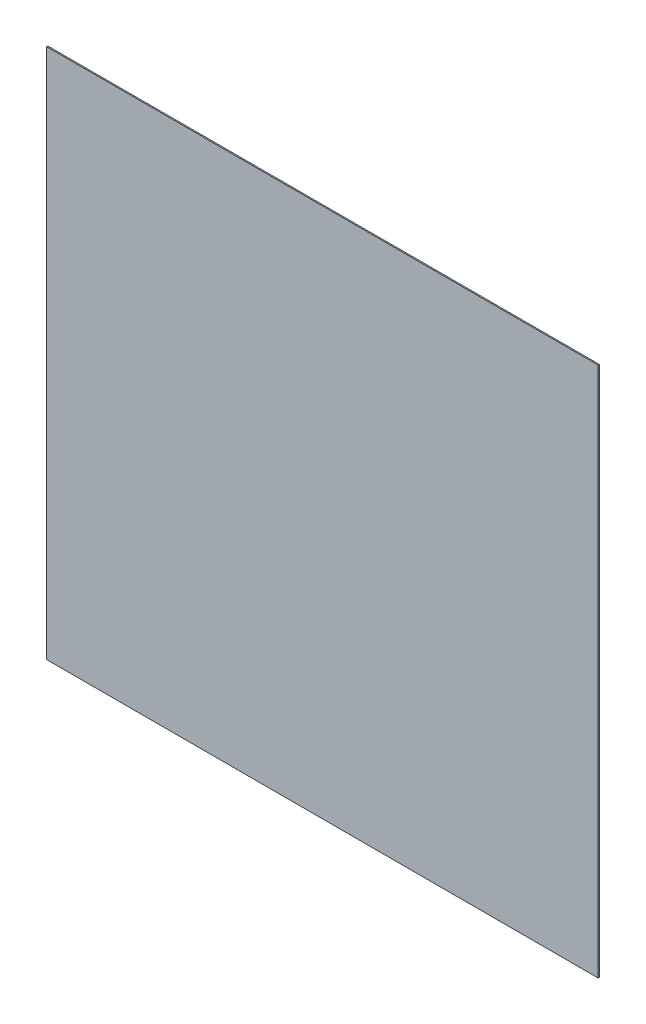
SolidWorks part; units mm, degrees
material "Acrylic (Medium-high impact)"
ref_plane "Front Plane" through (0, 0, 0) normal (0, 0, 1) x (1, 0, 0)
ref_plane "Top Plane" through (0, 0, 0) normal (0, 1, 0) x (1, 0, 0)
ref_plane "Right Plane" through (0, 0, 0) normal (1, 0, 0) x (0, 0, -1)
sketch "Sketch1" plane through (0, 0, 0) normal (0, 0, 1) x (1, 0, 0)
  line L1 (0, 0) -> (935, 0)
  line L2 (0, 0) -> (0, 900)
  line L3 (0, 900) -> (935, 900)
  line L4 (935, 0) -> (935, 900)
  dimension "D1" = 935
  dimension "D2" = 900
extrude "Boss-Extrude1" add sketch "Sketch1" along normal blind 2
